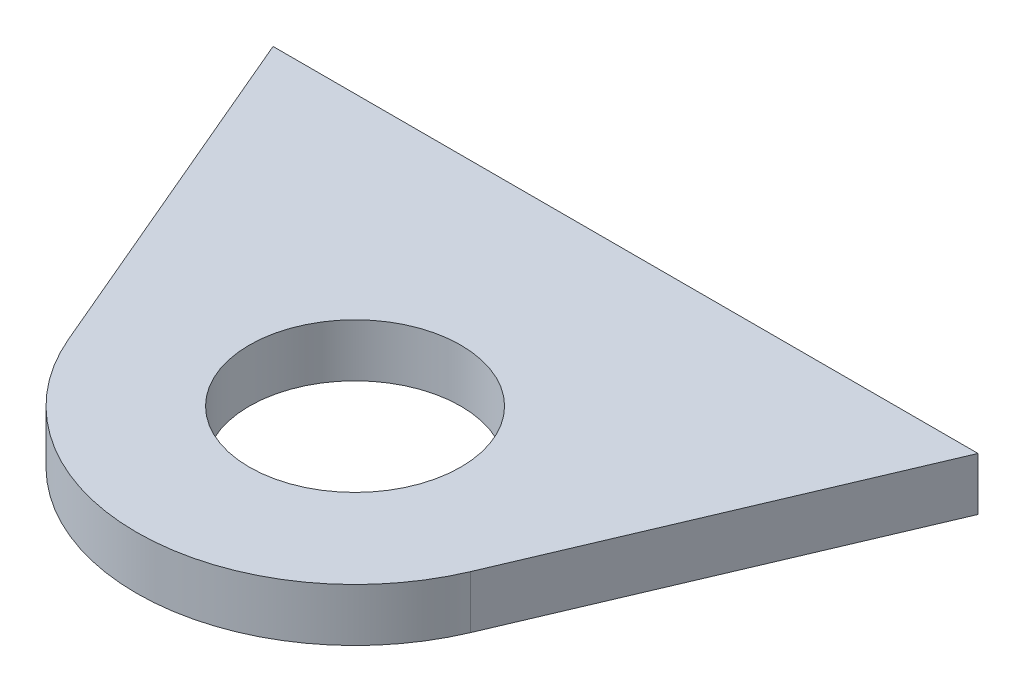
SolidWorks part; units mm, degrees
ref_plane "Front Plane" through (0, 0, 0) normal (0, 0, 1) x (1, 0, 0)
ref_plane "Top Plane" through (0, 0, 0) normal (0, 1, 0) x (1, 0, 0)
ref_plane "Right Plane" through (0, 0, 0) normal (1, 0, 0) x (0, 0, -1)
sketch "Sketch1" plane through (0, 0, 0) normal (0, 1, 0) x (1, 0, 0)
  line L0 (-20, 15.3481) -> (20, 15.3481)
  line L6 (-11.4114, -4.8519) -> (-20, 15.3481)
  line L7 (0, -18.9115) -> (0, 18.9115) construction
  line L8 (11.4114, -4.8519) -> (20, 15.3481)
  arc A2 (-11.4114, -4.8519) -> (11.4114, -4.8519) centre (0, 0) ccw
  circle A3 centre (0, 0) radius 6
  point P0 (0, 0)
  dimension "D1" = 40
  dimension "D2" = 6.4
  dimension "D3" = 12
extrude "Boss-Extrude1" add sketch "Sketch1" along normal blind 3
